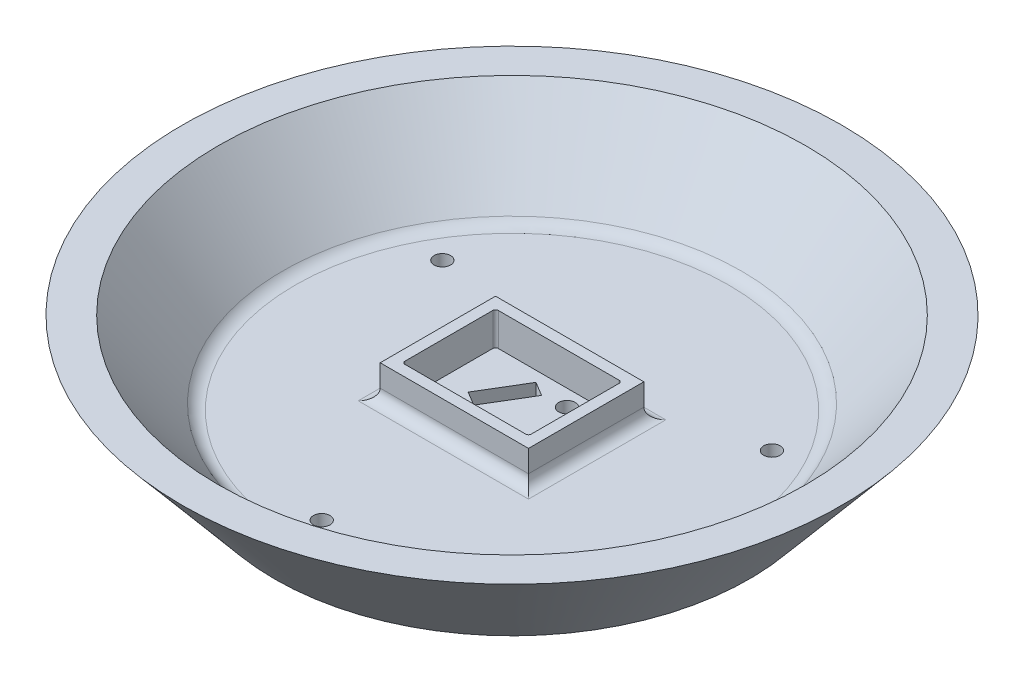
SolidWorks part; units mm, degrees
material "ABS"
ref_plane "Alzado" through (0, 0, 0) normal (0, 0, 1) x (1, 0, 0)
ref_plane "Planta" through (0, 0, 0) normal (0, 1, 0) x (1, 0, 0)
ref_plane "Vista lateral" through (0, 0, 0) normal (1, 0, 0) x (0, 0, -1)
sketch "Sketch1" plane through (0, 0, 0) normal (0, 1, 0) x (1, 0, 0)
  circle A0 centre (0, 0) radius 60
  dimension "D1" = 120
extrude "Boss-Extrude1" add sketch "Sketch1" against normal blind 20 draft 40
shell "Shell1" thickness 5
sketch "Sketch3" plane through (0, -15, 0) normal (0, 1, 0) x (1, 0, 0)
  line L1 (-11, 8.5) -> (11, 8.5)
  line L2 (-11.5, 8) -> (-11.5, -8)
  line L3 (-11, -8.5) -> (11, -8.5)
  line L4 (11.5, 8) -> (11.5, -8)
  line L5 (-11.5, 8.5) -> (11.5, -8.5) construction
  line L6 (-11.5, -8.5) -> (11.5, 8.5) construction
  line L10 (-13.5, -10.5) -> (13.5, -10.5)
  line L11 (13.5, 10.5) -> (13.5, -10.5)
  line L12 (-13.5, 10.5) -> (13.5, 10.5)
  line L13 (-13.5, 10.5) -> (-13.5, -10.5)
  line L14 (-13.5, -10.5) -> (13.5, -10.5) construction
  line L15 (-13.5, 10.5) -> (-13.5, -10.5) construction
  line L16 (13.5, 10.5) -> (13.5, -10.5) construction
  line L17 (-13.5, 10.5) -> (13.5, 10.5) construction
  line L18 (-11.5, 8.5) -> (-11.5, -8.5) construction
  line L19 (-11.5, -8.5) -> (11.5, -8.5) construction
  line L20 (11.5, 8.5) -> (11.5, -8.5) construction
  line L21 (-11.5, 8.5) -> (11.5, 8.5) construction
  arc A8 (-11.5, -8) -> (-11, -8.5) centre (-11, -8) ccw
  arc A9 (11, -8.5) -> (11.5, -8) centre (11, -8) ccw
  arc A10 (11, 8.5) -> (11.5, 8) centre (11, 8) cw
  arc A11 (-11, 8.5) -> (-11.5, 8) centre (-11, 8) ccw
  point P0 (0, 0)
  dimension "D5" = 0.5
  dimension "D1" = 17
  dimension "D2" = 23
  dimension "D3" = 2
extrude "Boss-Extrude2" add sketch "Sketch3" along normal blind 6
hole_wizard "Ø3.0mm Dowel Hole1" positions "Sketch4" profile "Sketch6" hole size "Ø3.0" standard "ANSI Metric"
sketch "Sketch4" plane through (0, -15, 0) normal (0, 1, 0) x (1, 0, 0)
  line L1 (0, 0) -> (0, -40.8865) construction
  line L3 (0, 0) -> (-35.4087, 20.4432) construction
  line L4 (0, 0) -> (35.4087, 20.4432) construction
  circle A1 centre (0, 0) radius 40.8865 construction
  point P0 (-29.9991, 17.32)
  point P19 (29.9991, 17.32)
  point P20 (0, -34.64)
  dimension "D1" = 34.64
  dimension "D2" = 34.64
  dimension "D5" = 34.64
  dimension "D3" = 3
  dimension "D4" = 3
sketch "Sketch6" plane through (-29.9991, -15, -17.32) normal (1, 0, 0) x (0, 0, 1)
  line L0 (0, 0) -> (0, 4.9013)
  line L1 (0, 4.9013) -> (1.5, 4)
  line L2 (1.5, 4) -> (1.5, 0)
  line L5 (1.5, 0) -> (0, 0)
  line L10 (0, 4.9013) -> (-1.5, 4) construction
  line L11 (0, -6.35) -> (0, 107.95) construction
  dimension "Hole Dia." = 3
  dimension "Hole Depth" = 4
  dimension "Drill Angle" = 118
hole_wizard "Ø3.0mm Dowel Hole2" positions "Sketch7" profile "Sketch8" hole size "Ø3.0" standard "ANSI Metric"
sketch "Sketch7" plane through (0, -15, 0) normal (0, 1, 0) x (1, 0, 0)
  line L0 (-11, -8.5) -> (11, -8.5) construction
  line L1 (11, 8.5) -> (-11, 8.5) construction
  line L2 (11.5, -8) -> (11.5, 8) construction
  point P0 (4.5, 5.5)
  point P2 (4.5, -6.5)
  dimension "D1" = 2
  dimension "D2" = 3
  dimension "D3" = 7
  dimension "D4" = 7
  dimension "D5" = 12
sketch "Sketch8" plane through (4.5, -15, -5.5) normal (1, 0, 0) x (0, 0, 1)
  line L0 (0, 0) -> (0, 10.9013)
  line L1 (0, 10.9013) -> (1.5, 10)
  line L2 (1.5, 10) -> (1.5, 0)
  line L5 (1.5, 0) -> (0, 0)
  line L10 (0, 10.9013) -> (-1.5, 10) construction
  line L11 (0, -6.35) -> (0, 107.95) construction
  dimension "Hole Dia." = 3
  dimension "Hole Depth" = 10
  dimension "Drill Angle" = 118
fillet "Fillet2" radius 2 4 edges at (0, -15, -10.5) (13.5, -15, 0) (0, -15, 10.5) (-13.5, -15, 0)
hole_wizard "Ø3.0mm Dowel Hole3" positions "Sketch9" profile "Sketch10" hole size "Ø3.0" standard "ANSI Metric"
sketch "Sketch9" plane through (0, -20, 0) normal (0, -1, 0) x (-1, 0, 0)
  line L0 (0, 0) -> (0, -43.218) construction
  line L2 (0, 0) -> (-37.4279, 21.609) construction
  line L3 (0, 0) -> (37.4279, 21.609) construction
  circle A0 centre (0, 0) radius 43.218 construction
  point P0 (0, -19)
  point P16 (-16.4545, 9.5)
  point P18 (16.4545, 9.5)
  dimension "D1" = 19
  dimension "D3" = 19
  dimension "D4" = 19
  dimension "D2" = 3
sketch "Sketch10" plane through (0, -20, 19) normal (1, 0, 0) x (0, 0, -1)
  line L0 (0, 0) -> (0, 4.9013)
  line L1 (0, 4.9013) -> (1.5, 4)
  line L2 (1.5, 4) -> (1.5, 0)
  line L5 (1.5, 0) -> (0, 0)
  line L10 (0, 4.9013) -> (-1.5, 4) construction
  line L11 (0, -6.35) -> (0, 107.95) construction
  dimension "Hole Dia." = 3
  dimension "Hole Depth" = 4
  dimension "Drill Angle" = 118
sketch "Sketch11" plane through (0, -20, 0) normal (0, -1, 0) x (1, 0, 0)
  line L5 (0.3419, -5.0467) -> (-2.2283, -6.594)
  line L6 (-2.2283, -6.594) -> (-6.8702, 1.1165)
  line L7 (-6.8702, 1.1165) -> (-4.3, 2.6639)
  line L8 (37.0261, 22.2905) -> (-37.0261, -22.2905) construction
  line L9 (0.3419, -5.0467) -> (-4.3, 2.6639)
  circle A0 centre (0, 0) radius 43.218 construction
  point P5 (-1.979, -1.1914)
  point P10 (-4.5492, -2.7387)
  point P12 (0, 0)
  dimension "D1" = 9
  dimension "D2" = 3
  dimension "D3" = 4.3
  dimension "D4" = 2.31
  dimension "D5" = 5.0467
  dimension "D6" = 3
  dimension "D7" = 1.1914
extrude "Cut-Extrude1" cut sketch "Sketch11" against normal blind 10 contours L5 L6 L7 L9
fillet "Fillet3" radius 3 1 edges at (0, -15, 40.8865)
